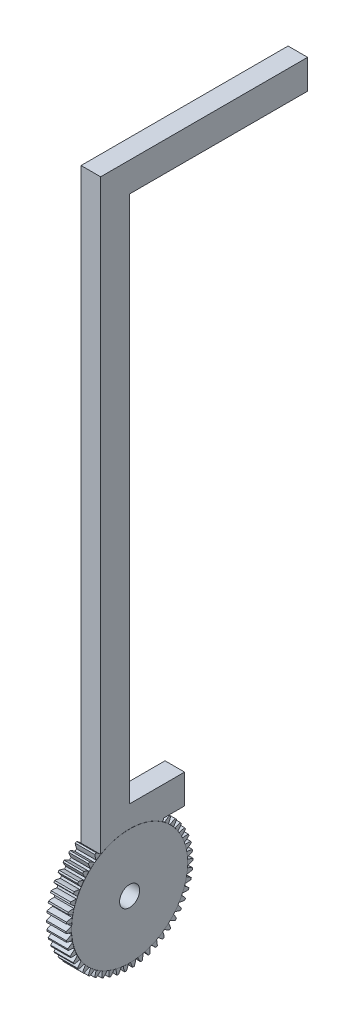
SolidWorks part; units mm, degrees
material "ABS"
ref_plane "Plane1" through (0, 0, 0) normal (0, 0, 1) x (1, 0, 0)
ref_plane "Plane2" through (0, 0, 0) normal (0, 1, 0) x (1, 0, 0)
ref_plane "Plane3" through (0, 0, 0) normal (1, 0, 0) x (0, 0, -1)
other "Center of Mass"
sketch "HoldingSke" plane through (0, 0, 0) normal (0, 1, 0) x (1, 0, 0)
  line L0 (0, 0) -> (2.5712, -3.0642)
  line L1 (-15, 0) -> (100, 0) construction
  line L2 (0, 0) -> (-2.1039, 2.3779)
  line L3 (0, 0) -> (-11.863, 4.5341)
  line L4 (0, 0) -> (5.5511, 6.6156)
  line L5 (0, 0) -> (-46.8476, -17.4728)
  line L6 (0, 0) -> (-1.6579, -1.1186)
  line L7 (-2.1039, 2.3779) -> (8.6586, 51.2059)
  line L8 (-76.2, 54.61) -> (-76.1, 54.61)
  line L9 (-71.009, 38.7566) -> (-53.1078, 45.2721)
  line L10 (-76.2, 71.12) -> (104.1128, 71.12)
  line L11 (0, 0) -> (-2, 0)
  line L12 (-76.2, 101.6) -> (-76.192, 101.6)
  line L13 (24.9733, 27.94) -> (52.9518, 28.4284)
  line L14 (24.9733, 27.94) -> (24.9743, 27.94)
  line L15 (24.9733, 27.94) -> (100.4006, 29.5858)
  line L16 (-63.627, -0.25) -> (-12.827, -0.25)
  circle A0 centre (0, 0) radius 0.5
  circle A1 centre (0, 0) radius 5.9365
  circle A2 centre (0, 0) radius 37.5
  circle A3 centre (0, 0) radius 0.5
  dimension "MHD" = 11.873
  dimension "Hub_dia" = 75
  dimension "Bore" = 1
  dimension "MBD" = 1
  dimension "Num_teeth" = 50
  dimension "Pitch" = 4
  dimension "Overall_len" = 50
  dimension "Show_teeth" = 50
  dimension "Thickness" = 2
  dimension "OAL" = 50.0001
  dimension "T_dim" = 0.1
  dimension "Ap" = 20
  dimension "H" = 19.05
  dimension "Pitch_radius" = 180.3128
  dimension "Width" = 2
  dimension "Backlash" = 0.008
  dimension "Addendum_fac" = 1
  dimension "Dedendum_fac" = 1.25
  dimension "Clearance_fac" = 0.25
  dimension "Dedendum_add" = 0.001
  dimension "Module" = 0.25
sketch "BasProSke" plane through (0, 0, 0) normal (0, 1, 0) x (1, 0, 0)
  line L0 (-10, 0) -> (60, 0) construction
  line L1 (0, 0) -> (0, 6.5)
  line L2 (0, 0) -> (2, 0)
  line L3 (2, 0) -> (2, 6.5)
  line L4 (2, 6.5) -> (0, 6.5)
  dimension "Thickness" = 2
  dimension "Diameter" = 13
revolve "Base-Revolve" add sketch "BasProSke" angle 360 about L0
sketch "TooCutSke" plane through (0, 0, 0) normal (1, 0, 0) x (0, 0, -1)
  line L1 (0, 0) -> (0, 107) construction
  line L2 (0, 0) -> (-0.2103, 6.2465) construction
  line L3 (0, 0) -> (-0.7845, 12.47) construction
  line L4 (-0.2103, 6.2465) -> (-0.3923, 6.235) construction
  arc A0 (0.1067, 5.9355) -> (-0.1067, 5.9355) centre (0, 0) ccw
  arc A1 (0.3398, 6.5165) -> (-0.3398, 6.5165) centre (0, 0) ccw
  circle A2 centre (0, 0) radius 6.25 construction
  circle A3 centre (0, 0) radius 5.8731 construction
  arc A4 (-0.1067, 5.9355) -> (-0.3398, 6.5165) centre (-2.5252, 5.3025) ccw
  arc A5 (0.3398, 6.5165) -> (0.1067, 5.9355) centre (2.5252, 5.3025) ccw
  dimension "Root_dia" = 11.873
  dimension "Overcut_dia" = 13.0508
  dimension "Pitch_dia" = 12.5
  dimension "Base_dia" = 11.7462
  dimension "Flank_rad" = 2.5
  dimension "Half_ang" = 3.6
  dimension "Half_CT" = 0.1823
extrude "ToothCut" cut sketch "TooCutSke" along normal through all
fillet "Breaks" [suppressed] radius 0.005
fillet "RootFillets" [suppressed] radius 0.0635
pattern_circular "TeethCuts" count 50 every 7.2 about axis through (-10, 0, 0) along (1, 0, 0) of "ToothCut", "RootFillets", "Breaks"
sketch "HubNeaOneSke" plane through (0, 0, 0) normal (-1, 0, 0) x (0, 0, 1)
  circle A0 centre (0, 0) radius 5.9365
  dimension "Diameter" = 11.873
extrude "HubNearOne" [suppressed] add sketch "HubNeaOneSke" along normal blind 48.0001
sketch "HubNeaBotSke" plane through (0, 0, 0) normal (-1, 0, 0) x (0, 0, 1)
  circle A0 centre (0, 0) radius 5.9365
  dimension "Diameter" = 11.873
extrude "HubNearBoth" [suppressed] add sketch "HubNeaBotSke" along normal blind 24
ref_plane "FarPln" through (2, 0, 0) normal (1, 0, 0) x (0, 0, -1)
sketch "HubFarSke" plane through (2, 0, 0) normal (1, 0, 0) x (0, 0, -1)
  circle A0 centre (0, 0) radius 5.9365
  dimension "Diameter" = 11.873
extrude "HubFar" [suppressed] add sketch "HubFarSke" along normal blind 24
sketch "BorSke" plane through (0, 0, 0) normal (1, 0, 0) x (0, 0, -1)
  circle A0 centre (0, 0) radius 0.5
  dimension "Diameter" = 1
extrude "Bore" cut sketch "BorSke" along normal mid plane 100.0001
sketch "KeySke" plane through (0, 0, 0) normal (1, 0, 0) x (0, 0, -1)
  line L0 (-0.05, 0) -> (-0.05, 0.6)
  line L1 (-0.05, 0.6) -> (0.05, 0.6)
  line L2 (0.05, 0.6) -> (0.05, 0)
  line L3 (0, 0) -> (0, 34) construction
  line L4 (-0.05, 0) -> (0.05, 0)
  dimension "Offset" = 0.6
  dimension "Width" = 0.1
extrude "Keyway" [suppressed] cut sketch "KeySke" along normal mid plane 100.0001
pattern_circular "Keyway2" [suppressed] count 2 every 90 about axis through (-10, 0, 0) along (1, 0, 0)
sketch "Sketch1" plane through (2, 0, 0) normal (1, 0, 0) x (0, 0, -1)
  line L0 (0, 0.5) -> (0, 5.9365)
  line L1 (0, 5.9365) -> (0, 11.2268)
  line L3 (-2.953, 5.1499) -> (2.953, 5.1499)
  line L5 (-2.953, 5.1499) -> (3.2527, 5.1499)
  line L9 (3.2527, 5.1499) -> (5.6313, 5.1499)
  line L11 (2.7061, 8.1499) -> (5.6313, 8.1499)
  line L12 (5.6313, 5.1499) -> (5.6313, 8.1499)
  line L13 (11.576, 65.1499) -> (18.2089, 65.1499)
  line L15 (12.7575, 62.1499) -> (18.2089, 62.1499)
  line L16 (18.2089, 65.1499) -> (18.2089, 62.1499)
  line L17 (-2.953, 5.1499) -> (-2.953, 65.1499)
  line L18 (-2.953, 65.1499) -> (11.576, 65.1499)
  line L19 (2.7061, 8.1499) -> (0, 8.1499)
  line L20 (0, 8.1499) -> (0, 62.1499)
  line L21 (12.7575, 62.1499) -> (0, 62.1499)
  circle A0 centre (0, 0) radius 0.5 construction
  arc A1 (0.1067, 5.9355) -> (-0.1067, 5.9355) centre (0, 0) ccw construction
  dimension "D1" = 60
  dimension "D3" = 3
  dimension "D5" = 3
extrude "Boss-Extrude1" add sketch "Sketch1" against normal blind 2 contours L5 L9 L12 L11 L19 L20 L21 L15 L16 L13 L18 L17
sketch "Sketch2" plane through (2, 0, 0) normal (1, 0, 0) x (0, 0, -1)
  circle A0 centre (0, 0) radius 1.025
  dimension "D1" = 2.05
extrude "Cut-Extrude1" cut sketch "Sketch2" against normal blind 10
ref_plane "Plane4" through (1, 0, 0) normal (1, 0, 0) x (0, 0, -1)
ref_point "CenterOfRotation"
sketch "Sketch3" plane through (2, 0, 0) normal (1, 0, 0) x (0, 0, -1)
  circle A0 centre (0, 0) radius 1.025 construction
  circle A1 centre (0, 0) radius 1.025
  circle A2 centre (0, 0) radius 5.9365
extrude "Boss-Extrude2" add sketch "Sketch3" along normal blind 0.01
equation "' \"Module@HoldingSke\" = 6.35"
equation "' \"Num_teeth@HoldingSke\" = 12"
equation "' \"Ap@HoldingSke\" =  20"
equation "' \"Ap@HoldingSke\" = 20"
equation "' \"Width@HoldingSke\" = 0.5 * 25.4"
equation "' \"Hub_dia@HoldingSke\"= 1 * 25.4"
equation "' \"Hub_dia@HoldingSke\" = 1 * 25.4"
equation "' \"Overall_len@HoldingSke\" = 1.0 * 25.4"
equation "' \"Bore@HoldingSke\" = 0.75 * 25.4"
equation "' \"T_dim@HoldingSke\" = 0.1 * 25.4"
equation "' \"Width@KeySke\" = 0.25 * 25.4"
equation "' \"Show_teeth@HoldingSke\" = 13"
equation "' \"Backlash@HoldingSke\" = 0.009 * 25.4"
equation "' \"Addendum_fac@HoldingSke\" = 1.0"
equation "' \"Dedendum_fac@HoldingSke\" = 1.25"
equation "' \"Dedendum_add@HoldingSke\" = 0.00005 * 25.4"
equation "' \"Clearance_fac@HoldingSke\" = 0.25"
equation "\"Pitch@HoldingSke\" = 1 / \"Module@HoldingSke\""
equation "\"Overcut_dia@TooCutSke\" = (\"Num_teeth@HoldingSke\" + 2 * \"Addendum_fac@HoldingSke\") / \"Pitch@HoldingSke\" + 0.002 * 25.4"
equation "\"Pitch_dia@TooCutSke\" = \"Num_teeth@HoldingSke\" / \"Pitch@HoldingSke\""
equation "\"Base_dia@TooCutSke\" = \"Num_teeth@HoldingSke\" / \"Pitch@HoldingSke\" * cos((\"Ap@HoldingSke\"  * 3.14159265 / 180))"
equation "\"Root_dia@TooCutSke\" = (\"Num_teeth@HoldingSke\" + 2) / \"Pitch@HoldingSke\" - 2 * (\"Addendum_fac@HoldingSke\" + \"Dedendum_fac@HoldingSke\") / \"Pitch@HoldingSke\" - \"Dedendum_add@HoldingSke\" * 2"
equation "\"Half_ang@TooCutSke\" = 180 / \"Num_teeth@HoldingSke\""
equation "\"Half_CT@TooCutSke\" = \"Num_teeth@HoldingSke\" / \"Pitch@HoldingSke\" * sin((3.14159265 / 2 / \"Num_teeth@HoldingSke\")) / 2 - 7 * \"Backlash@HoldingSke\" / 4"
equation "\"Flank_rad@TooCutSke\" = \"Num_teeth@HoldingSke\" / \"Pitch@HoldingSke\" / 5"
equation "\"Radius@RootFillets\" = \"Clearance_fac@HoldingSke\" / \"Pitch@HoldingSke\" + \"Dedendum_add@HoldingSke\""
equation "\"Break_rad@Breaks\" = 0.02 / \"Pitch@HoldingSke\""
equation "\"Thickness@HoldingSke\" = \"Width@HoldingSke\""
equation "\"OAL@HoldingSke\" = \"Thickness@HoldingSke\""
equation "\"MHD@HoldingSke\" = (\"Num_teeth@HoldingSke\" + 2) / \"Pitch@HoldingSke\" - 2 * (\"Addendum_fac@HoldingSke\" + \"Dedendum_fac@HoldingSke\")  / \"Pitch@HoldingSke\" - \"Dedendum_add@HoldingSke\" * 2"
equation "\"MBD@HoldingSke\" = (\"Num_teeth@HoldingSke\" + 2) / \"Pitch@HoldingSke\" - 2 * (\"Addendum_fac@HoldingSke\" + \"Dedendum_fac@HoldingSke\")  / \"Pitch@HoldingSke\" - \"Dedendum_add@HoldingSke\" * 2 - 0.002 * 25.4"
equation "\"MHD@HoldingSke\" = ((sgn( \"MHD@HoldingSke\" - \"Hub_dia@HoldingSke\" )-1)*( \"MHD@HoldingSke\" - \"Hub_dia@HoldingSke\" ))/-2+ \"Hub_dia@HoldingSke\""
equation "\"MBD@HoldingSke\" = ((sgn( \"MBD@HoldingSke\" - \"Bore@HoldingSke\" )-1)*( \"MBD@HoldingSke\" - \"Bore@HoldingSke\" ))/-2+ \"Bore@HoldingSke\""
equation "\"OAL@HoldingSke\" = ((sgn( \"OAL@HoldingSke\" - \"Overall_len@HoldingSke\" )+1)*( \"OAL@HoldingSke\" - \"Overall_len@HoldingSke\" ))/2 + \"Overall_len@HoldingSke\" + 0.000002 * 25.4"
equation "\"Num_teeth@TeethCuts\" = int( \"Show_teeth@HoldingSke\" ) + 1"
equation "\"Num_teeth@TeethCuts\" = ((sgn( \"Num_teeth@TeethCuts\" - \"Num_teeth@HoldingSke\" )-1)*( \"Num_teeth@TeethCuts\" - \"Num_teeth@HoldingSke\" ))/-2+ \"Num_teeth@HoldingSke\""
equation "\"Num_teeth@TeethCuts\" = ((sgn( \"Num_teeth@TeethCuts\" - 2.0)+1)*( \"Num_teeth@TeethCuts\" - 2.0))/2 +2.0"
equation "\"Angle@TeethCuts\" = 360.0 / \"Num_teeth@HoldingSke\""
equation "\"Diameter@BasProSke\" = (\"Num_teeth@HoldingSke\" + 2 * \"Addendum_fac@HoldingSke\") / \"Pitch@HoldingSke\""
equation "\"Thickness@BasProSke\"  = \"Thickness@HoldingSke\""
equation "' \"Fillet_rad@BasProSke\" =  \"Thickness@HoldingSke\" * 0.05"
equation "' \"Fillet_rad@BasProSke\" = \"Thickness@HoldingSke\" * 0.05"
equation "\"MHD@HoldingSke\" = ((sgn( \"MHD@HoldingSke\" - \"Root_dia@TooCutSke\" )-1)*( \"MHD@HoldingSke\" - \"Root_dia@TooCutSke\" ))/-2+ \"Root_dia@TooCutSke\""
equation "\"Diameter@HubNeaOneSke\" = \"MHD@HoldingSke\""
equation "\"Length@HubNearOne\" = \"OAL@HoldingSke\" - \"Thickness@BasProSke\""
equation "\"Diameter@HubNeaBotSke\" = \"MHD@HoldingSke\""
equation "\"Length@HubNearBoth\" = ( \"OAL@HoldingSke\" - \"Thickness@BasProSke\" ) / 2.0"
equation "\"Thickness@FarPln\" = \"Thickness@BasProSke\""
equation "\"Diameter@HubFarSke\" = \"MHD@HoldingSke\""
equation "\"Length@HubFar\" = ( \"OAL@HoldingSke\" - \"Thickness@BasProSke\" ) / 2.0"
equation "\"Diameter@BorSke\" = \"MBD@HoldingSke\""
equation "\"D1@Bore\" = \"OAL@HoldingSke\" * 2.0"
equation "\"D1@Keyway\" = \"OAL@HoldingSke\" * 2.0"
equation "\"Offset@KeySke\" = \"T_dim@HoldingSke\" + \"MBD@HoldingSke\" / 2.0"
